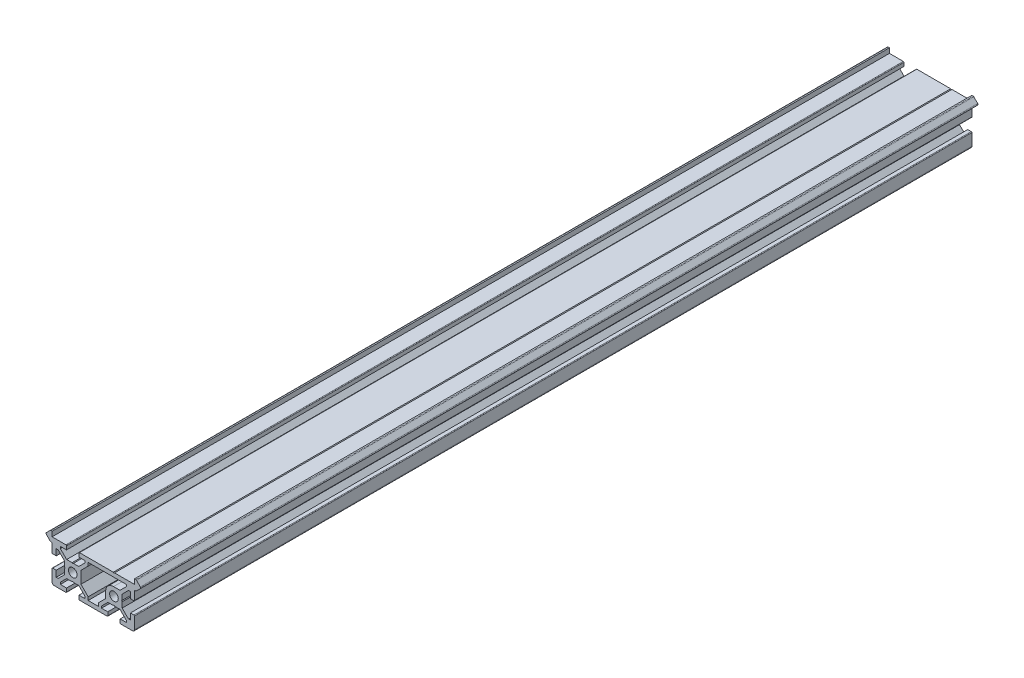
SolidWorks part; units mm, degrees
ref_plane "Front Plane" through (0, 0, 0) normal (0, 0, 1) x (1, 0, 0)
ref_plane "Top Plane" through (0, 0, 0) normal (0, 1, 0) x (1, 0, 0)
ref_plane "Right Plane" through (0, 0, 0) normal (1, 0, 0) x (0, 0, -1)
sketch "Model" plane through (0, 0, 0) normal (0, 0, 1) x (1, 0, 0)
  line L0 (0, 0) -> (0, 76.2) construction
  line L1 (0, 0) -> (101.6, 0) construction
  line L2 (0, 76.2) -> (101.6, 76.2) construction
  line L3 (101.6, 0) -> (101.6, 76.2) construction
  line L4 (28.7715, 48.1056) -> (30.6465, 49.9806)
  line L5 (31.5929, 50.127) -> (31.5929, 47.752)
  line L6 (31.5929, 44.877) -> (31.5929, 41.052)
  line L7 (31.5929, 34.452) -> (31.5929, 28.752)
  line L8 (33.5929, 31.752) -> (33.5929, 34.752)
  line L9 (33.5929, 40.752) -> (33.5929, 43.752)
  line L10 (35.5929, 29.752) -> (35.5929, 30.6914)
  line L11 (35.5929, 44.8127) -> (35.5929, 45.752)
  line L12 (37.5929, 40.6914) -> (37.5929, 38.052)
  line L13 (37.5929, 37.452) -> (37.5929, 34.8127)
  line L14 (38.5929, 28.052) -> (38.5929, 29.752)
  line L15 (38.5929, 45.752) -> (38.5929, 47.452)
  line L16 (32.5929, 27.752) -> (38.2929, 27.752)
  line L17 (44.8929, 27.752) -> (58.2929, 27.752)
  line L18 (64.8929, 27.752) -> (70.5929, 27.752)
  line L19 (37.5929, 38.052) -> (37.8929, 37.752)
  line L20 (41.5929, 34.052) -> (41.8929, 33.752)
  line L21 (30.6465, 45.5235) -> (28.7715, 47.3985)
  line L22 (41.8929, 41.752) -> (41.5929, 41.452)
  line L23 (37.8929, 37.752) -> (37.5929, 37.452)
  line L24 (67.5929, 29.752) -> (64.5929, 29.752)
  line L25 (58.5929, 29.752) -> (55.5929, 29.752)
  line L26 (54.0929, 29.752) -> (49.0929, 29.752)
  line L27 (47.5929, 29.752) -> (44.5929, 29.752)
  line L28 (38.5929, 29.752) -> (35.5929, 29.752)
  line L29 (34.5323, 43.752) -> (37.5929, 40.6914)
  line L30 (44.5323, 33.752) -> (47.5929, 30.6914)
  line L31 (44.5929, 47.452) -> (44.5929, 45.752)
  line L32 (44.5929, 29.752) -> (44.5929, 28.052)
  line L33 (47.5929, 44.8127) -> (44.5323, 41.752)
  line L34 (37.5929, 34.8127) -> (34.5323, 31.752)
  line L35 (69.5929, 31.752) -> (68.6536, 31.752)
  line L36 (34.5323, 31.752) -> (33.5929, 31.752)
  line L37 (49.0929, 31.3127) -> (45.5929, 34.8127)
  line L38 (38.6536, 41.752) -> (35.5929, 44.8127)
  line L39 (45.5929, 34.8127) -> (45.5929, 40.6914)
  line L40 (35.5929, 30.6914) -> (38.6536, 33.752)
  line L41 (45.5929, 40.6914) -> (49.0929, 44.1914)
  line L42 (38.6536, 33.752) -> (41.2929, 33.752)
  line L43 (41.8929, 33.752) -> (44.5323, 33.752)
  line L44 (58.6536, 33.752) -> (61.2929, 33.752)
  line L45 (61.8929, 33.752) -> (64.5323, 33.752)
  line L46 (41.5929, 41.452) -> (41.2929, 41.752)
  line L47 (47.5929, 45.752) -> (47.5929, 44.8127)
  line L48 (47.5929, 30.6914) -> (47.5929, 29.752)
  line L49 (41.2929, 33.752) -> (41.5929, 34.052)
  line L50 (71.2929, 34.752) -> (69.5929, 34.752)
  line L51 (33.5929, 34.752) -> (31.8929, 34.752)
  line L52 (49.0929, 29.752) -> (49.0929, 31.3127)
  line L53 (49.0929, 44.1914) -> (49.0929, 45.752)
  line L54 (61.5929, 47.452) -> (61.8929, 47.752)
  line L55 (31.8929, 40.752) -> (33.5929, 40.752)
  line L56 (69.5929, 40.752) -> (71.2929, 40.752)
  line L57 (54.0929, 31.3127) -> (54.0929, 29.752)
  line L58 (64.5323, 41.752) -> (61.4029, 41.752)
  line L59 (44.5323, 41.752) -> (41.8929, 41.752)
  line L60 (41.2929, 41.752) -> (38.6536, 41.752)
  line L61 (61.5929, 34.052) -> (61.8929, 33.752)
  line L62 (55.5929, 29.752) -> (55.5929, 30.6914)
  line L63 (33.5929, 43.752) -> (34.5323, 43.752)
  line L64 (68.6536, 43.752) -> (69.5929, 43.752)
  line L65 (57.5929, 37.942) -> (57.5929, 34.8127)
  line L66 (58.5929, 28.052) -> (58.5929, 29.752)
  line L67 (31.0929, 45.377) -> (31, 45.377)
  line L68 (72.0929, 45.377) -> (72.1858, 45.377)
  line L69 (35.5929, 45.752) -> (38.5929, 45.752)
  line L70 (44.5929, 45.752) -> (47.5929, 45.752)
  line L71 (49.0929, 45.752) -> (67.5929, 45.752)
  line L72 (64.5323, 33.752) -> (67.5929, 30.6914)
  line L73 (68.6536, 31.752) -> (65.5929, 34.8127)
  line L74 (67.5929, 44.8127) -> (64.5323, 41.752)
  line L75 (57.5929, 34.8127) -> (54.0929, 31.3127)
  line L76 (55.5929, 30.6914) -> (58.6536, 33.752)
  line L77 (65.5929, 40.6914) -> (68.6536, 43.752)
  line L78 (72.5394, 45.5235) -> (74.4144, 47.3985)
  line L79 (71.5929, 47.752) -> (61.8929, 47.752)
  line L80 (61.2929, 47.752) -> (44.8929, 47.752)
  line L81 (38.2929, 47.752) -> (31.5929, 47.752)
  line L82 (65.5929, 37.452) -> (65.2929, 37.752)
  line L83 (61.2929, 33.752) -> (61.5929, 34.052)
  line L84 (65.2929, 37.752) -> (65.5929, 38.052)
  line L85 (72.1858, 50.127) -> (71.5929, 50.127)
  line L86 (31, 50.127) -> (31.5929, 50.127)
  line L87 (64.5929, 29.752) -> (64.5929, 28.052)
  line L88 (61.2929, 47.752) -> (61.5929, 47.452)
  line L89 (65.5929, 34.8127) -> (65.5929, 37.452)
  line L90 (65.5929, 38.052) -> (65.5929, 40.6914)
  line L91 (67.5929, 45.752) -> (67.5929, 44.8127)
  line L92 (67.5929, 30.6914) -> (67.5929, 29.752)
  line L93 (69.5929, 43.752) -> (69.5929, 40.752)
  line L94 (69.5929, 34.752) -> (69.5929, 31.752)
  line L95 (71.5929, 50.127) -> (71.5929, 47.752)
  line L96 (71.5929, 28.752) -> (71.5929, 34.452)
  line L97 (71.5929, 41.052) -> (71.5929, 44.877)
  line L98 (74.4144, 48.1056) -> (72.5394, 49.9806)
  arc A0 (61.4029, 41.752) -> (57.5929, 37.942) centre (61.4029, 37.942) ccw
  circle A1 centre (61.5929, 37.752) radius 2.1
  circle A2 centre (41.5929, 37.752) radius 2.1
  arc A3 (31.5929, 28.752) -> (32.5929, 27.752) centre (32.5929, 28.752) ccw
  arc A4 (70.5929, 27.752) -> (71.5929, 28.752) centre (70.5929, 28.752) ccw
  arc A5 (31.5929, 44.877) -> (31.0929, 45.377) centre (31.0929, 44.877) ccw
  arc A6 (72.0929, 45.377) -> (71.5929, 44.877) centre (72.0929, 44.877) ccw
  arc A7 (31, 50.127) -> (30.6465, 49.9806) centre (31, 49.627) ccw
  arc A8 (28.7715, 48.1056) -> (28.7715, 47.3985) centre (29.125, 47.752) ccw
  arc A9 (30.6465, 45.5235) -> (31, 45.377) centre (31, 45.877) ccw
  arc A10 (72.5394, 49.9806) -> (72.1858, 50.127) centre (72.1858, 49.627) ccw
  arc A11 (74.4144, 47.3985) -> (74.4144, 48.1056) centre (74.0608, 47.752) ccw
  arc A12 (72.1858, 45.377) -> (72.5394, 45.5235) centre (72.1858, 45.877) ccw
  arc A13 (31.8929, 34.752) -> (31.5929, 34.452) centre (31.8929, 34.452) ccw
  arc A14 (44.8929, 47.752) -> (44.5929, 47.452) centre (44.8929, 47.452) ccw
  arc A15 (38.5929, 47.452) -> (38.2929, 47.752) centre (38.2929, 47.452) ccw
  arc A16 (31.5929, 41.052) -> (31.8929, 40.752) centre (31.8929, 41.052) ccw
  arc A17 (38.2929, 27.752) -> (38.5929, 28.052) centre (38.2929, 28.052) ccw
  arc A18 (44.5929, 28.052) -> (44.8929, 27.752) centre (44.8929, 28.052) ccw
  arc A19 (58.2929, 27.752) -> (58.5929, 28.052) centre (58.2929, 28.052) ccw
  arc A20 (64.5929, 28.052) -> (64.8929, 27.752) centre (64.8929, 28.052) ccw
  arc A21 (71.5929, 34.452) -> (71.2929, 34.752) centre (71.2929, 34.452) ccw
  arc A22 (71.2929, 40.752) -> (71.5929, 41.052) centre (71.2929, 41.052) ccw
extrude "Boss-Extrude1" add sketch "Model" along normal offset from surface (406.36 mm away) 40 from offset 40
ref_plane "Plane1" through (51.5929, 0, 0) normal (-1, 0, 0) x (0, 0, 1)
